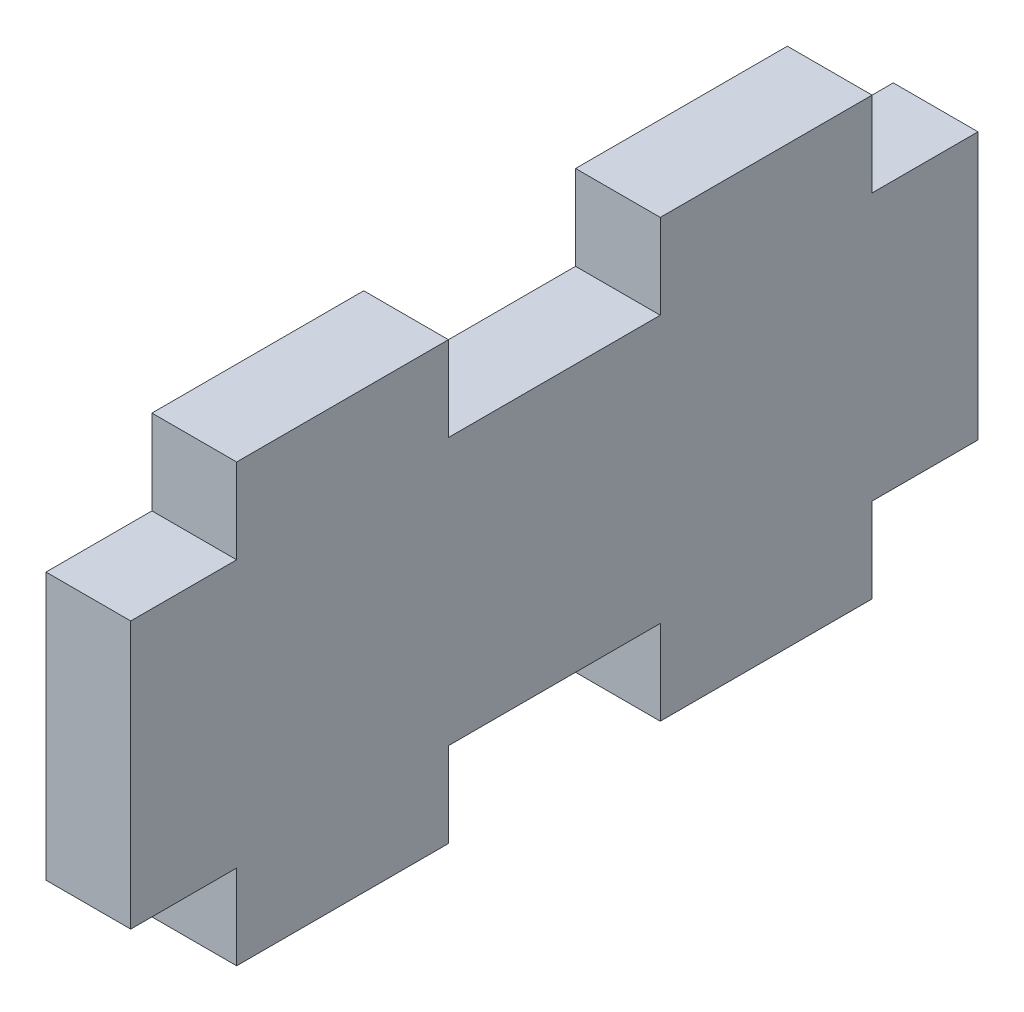
SolidWorks part; units mm, degrees
ref_plane "Front Plane" through (0, 0, 0) normal (0, 0, 1) x (1, 0, 0)
ref_plane "Top Plane" through (0, 0, 0) normal (0, 1, 0) x (1, 0, 0)
ref_plane "Right Plane" through (0, 0, 0) normal (1, 0, 0) x (0, 0, -1)
sketch "Sketch1" plane through (0, 0, 0) normal (1, 0, 0) x (0, 0, -1)
  line L0 (-7.5, 3.15) -> (-7.5, 5.15)
  line L1 (-10, 3.15) -> (-7.5, 3.15)
  line L2 (-10, 3.15) -> (-10, -3.15)
  line L3 (-10, -3.15) -> (-7.5, -3.15)
  line L4 (10, 3.15) -> (10, -3.15)
  line L5 (-10, 3.15) -> (10, -3.15) construction
  line L6 (-10, -3.15) -> (10, 3.15) construction
  line L7 (-7.5, 5.15) -> (-2.5, 5.15)
  line L8 (-2.5, 5.15) -> (-2.5, 3.15)
  line L9 (2.5, 3.15) -> (2.5, 5.15)
  line L10 (2.5, 5.15) -> (7.5, 5.15)
  line L11 (7.5, 5.15) -> (7.5, 3.15)
  line L12 (-2.5, 3.15) -> (2.5, 3.15)
  line L13 (7.5, 3.15) -> (10, 3.15)
  line L14 (-7.5, -3.15) -> (-7.5, -5.15)
  line L15 (-7.5, -5.15) -> (-2.5, -5.15)
  line L16 (-2.5, -5.15) -> (-2.5, -3.15)
  line L17 (7.5, -3.15) -> (7.5, -5.15)
  line L18 (7.5, -5.15) -> (2.5, -5.15)
  line L19 (2.5, -5.15) -> (2.5, -3.15)
  line L20 (-2.5, -3.15) -> (2.5, -3.15)
  line L21 (7.5, -3.15) -> (10, -3.15)
  point P0 (0, 0)
  point P12 (-5, 5.15)
  point P15 (5, 5.15)
  dimension "D1" = 6.3
  dimension "D2" = 20
  dimension "D3" = 5
  dimension "D4" = 2
  dimension "D5" = 5
  dimension "D6" = 5
  dimension "D7" = 2
  dimension "D8" = 5
  dimension "D9" = 2
  dimension "D10" = 2
extrude "Boss-Extrude1" add sketch "Sketch1" along normal blind 2
